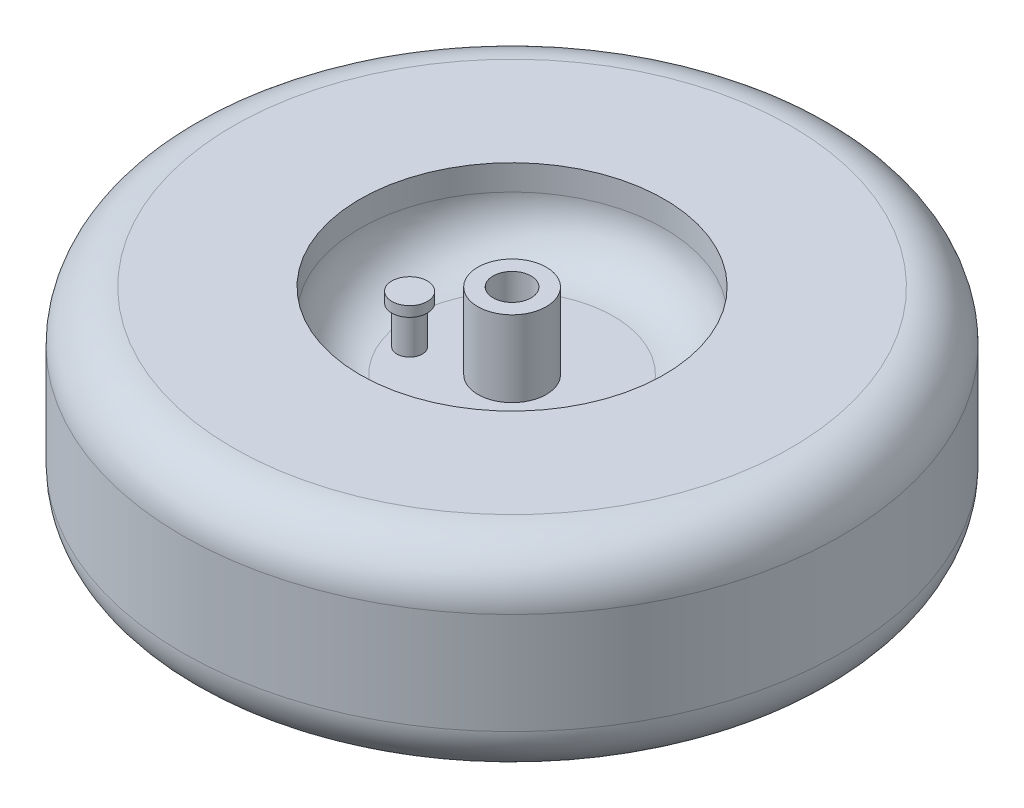
SolidWorks part; units mm, degrees
material "Rubber"
ref_plane "Front Plane" through (0, 0, 0) normal (0, 0, 1) x (1, 0, 0)
ref_plane "Top Plane" through (0, 0, 0) normal (0, 1, 0) x (1, 0, 0)
ref_plane "Right Plane" through (0, 0, 0) normal (1, 0, 0) x (0, 0, -1)
sketch "Sketch1" plane through (0, 0, 0) normal (0, 1, 0) x (1, 0, 0)
  circle A0 centre (0, 0) radius 165.1
  dimension "D1" = 330.2
extrude "Boss-Extrude2" add sketch "Sketch1" along normal blind 101.6
sketch "Sketch2" plane through (0, 101.6, 0) normal (0, 1, 0) x (1, 0, 0)
  circle A0 centre (0, 0) radius 76.2
extrude "Cut-Extrude1" cut sketch "Sketch2" against normal blind 38.1
fillet "Fillet3" radius 25.4 1 edges at (0, 63.5, 76.2)
fillet "Fillet4" radius 25.4 1 edges at (0, 101.6, 165.1)
sketch "Sketch3" plane through (0, 0, 0) normal (0, -1, 0) x (-1, 0, 0)
  circle A0 centre (0, 0) radius 76.2
extrude "Cut-Extrude2" cut sketch "Sketch3" against normal blind 38.1
fillet "Fillet5" radius 25.4 1 edges at (0, 38.1, -76.2)
fillet "Fillet6" radius 25.4 1 edges at (0, 0, 165.1)
sketch "Sketch4" plane through (0, 38.1, 0) normal (0, -1, 0) x (-1, 0, 0)
  circle A0 centre (0, 0) radius 17.145
extrude "Boss-Extrude3" add sketch "Sketch4" along normal blind 38.1
sketch "Sketch5" plane through (0, 63.5, 0) normal (0, 1, 0) x (1, 0, 0)
  circle A0 centre (0, 0) radius 17.145
extrude "Boss-Extrude4" add sketch "Sketch5" along normal blind 38.1
sketch "Sketch6" plane through (0, 101.6, 0) normal (0, 1, 0) x (1, 0, 0)
  circle A0 centre (0, 0) radius 9.525
extrude "Cut-Extrude3" cut sketch "Sketch6" against normal through all
sketch "Sketch7" plane through (0, 63.5, 0) normal (0, 1, 0) x (1, 0, 0)
  circle A0 centre (-37.7856, -13.5479) radius 6.35
extrude "Boss-Extrude5" add sketch "Sketch7" along normal blind 19.05
sketch "Sketch8" plane through (0, 82.55, 0) normal (0, 1, 0) x (1, 0, 0)
  circle A0 centre (-37.7856, -13.5479) radius 8.89
extrude "Boss-Extrude6" add sketch "Sketch8" along normal blind 5.08
